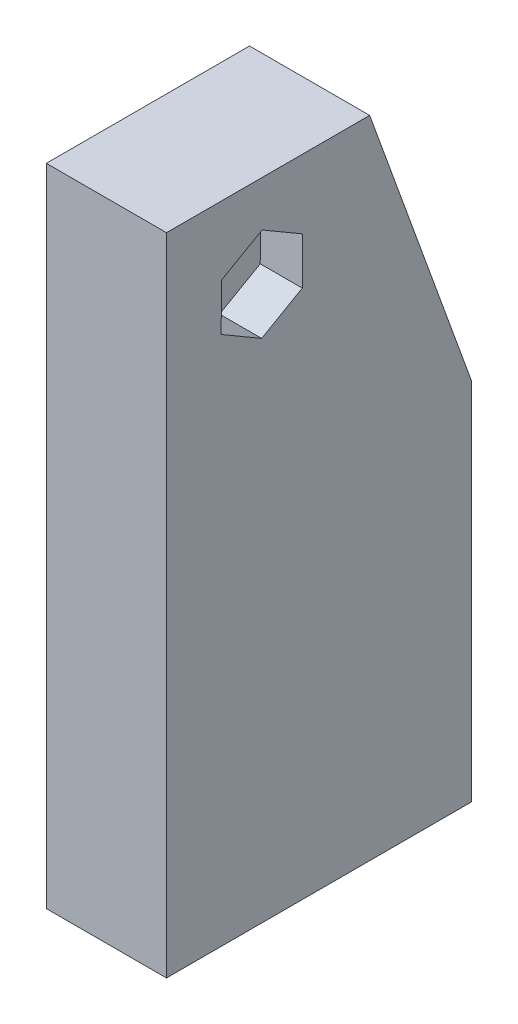
SolidWorks part; units mm, degrees
ref_plane "Front" through (0, 0, 0) normal (0, 0, 1) x (1, 0, 0)
ref_plane "Top" through (0, 0, 0) normal (0, 1, 0) x (1, 0, 0)
ref_plane "Right" through (0, 0, 0) normal (1, 0, 0) x (0, 0, -1)
sketch "Sketch1" plane through (0, 0, 0) normal (0, 0, 1) x (1, 0, 0)
  line L0 (104.7484, -27.117) -> (104.7484, -134.5537)
  line L1 (104.7484, -134.5537) -> (84.7484, -134.5537)
  line L2 (84.7484, -134.5537) -> (84.7484, -27.117)
  line L3 (84.7484, -27.117) -> (104.7484, -27.117)
  line L4 (89.6039, -26.617) -> (80.1571, -26.617) construction
  line L5 (-159.7042, -134.5537) -> (-172.4042, -134.5537) construction
  point P6 (84.8805, -26.617)
  dimension "D1" = 0.5
  dimension "D2" = 0
  dimension "D3" = 20
extrude "Boss-Extrude1" add sketch "Sketch1" against normal blind 50.8
sketch "Sketch3" plane through (84.7484, 0, 0) normal (-1, 0, 0) x (0, 0, 1)
  line L1 (-9.1448, -38.5475) -> (-15.9144, -34.6846)
  line L2 (-15.9144, -34.6846) -> (-22.6446, -38.6157)
  line L3 (-22.6446, -38.6157) -> (-22.6052, -46.4099)
  line L4 (-22.6052, -46.4099) -> (-15.8356, -50.2728)
  line L5 (-15.8356, -50.2728) -> (-9.1054, -46.3416)
  line L6 (-9.1054, -46.3416) -> (-9.1448, -38.5475)
  circle A0 centre (-15.875, -42.4787) radius 6.75 construction
extrude "Cut-Extrude2" cut sketch "Sketch3" against normal blind 7
sketch "Sketch4" plane through (104.7484, 0, 0) normal (1, 0, 0) x (0, 0, -1)
  line L0 (15.8356, -50.2728) -> (9.1054, -46.3416) construction
  line L1 (9.1054, -46.3416) -> (9.1448, -38.5475) construction
  line L2 (9.1448, -38.5475) -> (15.9144, -34.6846) construction
  line L3 (15.9144, -34.6846) -> (22.6446, -38.6157) construction
  line L4 (22.6446, -38.6157) -> (22.6052, -46.4099) construction
  line L5 (22.6052, -46.4099) -> (15.8356, -50.2728) construction
  line L6 (15.8356, -50.2728) -> (9.1054, -46.3416)
  line L7 (9.1054, -46.3416) -> (9.1448, -38.5475)
  line L8 (9.1448, -38.5475) -> (15.9144, -34.6846)
  line L9 (15.9144, -34.6846) -> (22.6446, -38.6157)
  line L10 (22.6446, -38.6157) -> (22.6052, -46.4099)
  line L11 (22.6052, -46.4099) -> (15.8356, -50.2728)
extrude "Cut-Extrude3" cut sketch "Sketch4" against normal blind 7
sketch "Sketch5" plane through (84.7484, 0, 0) normal (-1, 0, 0) x (0, 0, 1)
  line L0 (-33.8187, -27.117) -> (-50.8, -73.9384)
  line L1 (-50.8, -27.117) -> (0, -27.117) construction
  line L2 (-50.8, -27.117) -> (-50.8, -134.5537) construction
  line L3 (-50.8, -73.9384) -> (-50.97, -27.1156)
  line L4 (-50.97, -27.1156) -> (-33.8187, -27.117)
  dimension "D1" = 46.8227
  dimension "D2" = 17.1513
extrude "Cut-Extrude4" cut sketch "Sketch5" against normal up to next
